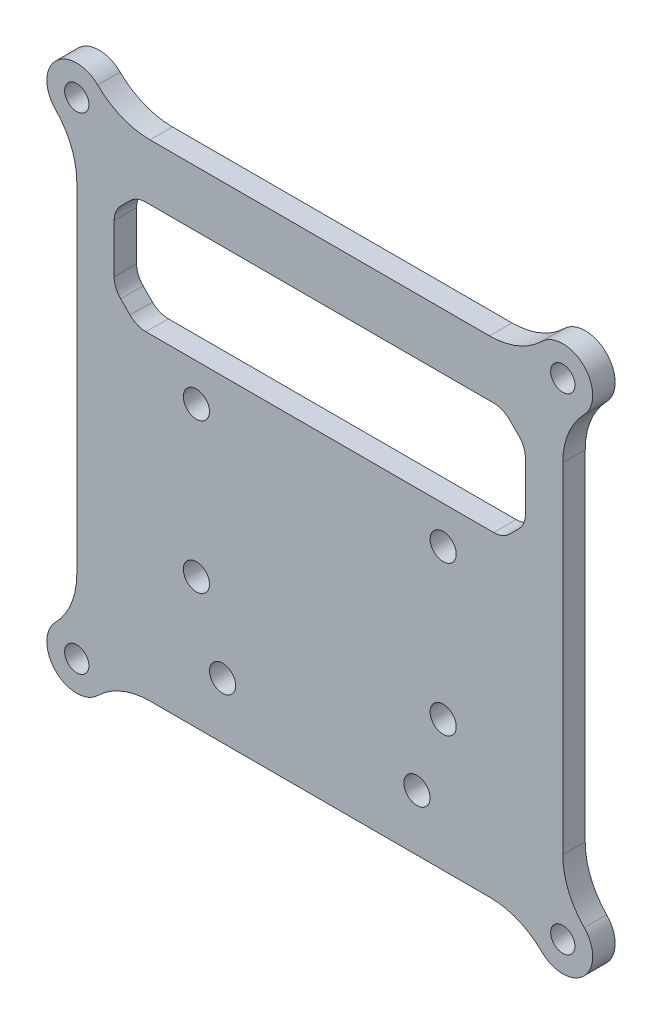
SolidWorks part; units mm, degrees
material "ABS"
ref_plane "Спереди" through (0, 0, 0) normal (0, 0, 1) x (1, 0, 0)
ref_plane "Сверху" through (0, 0, 0) normal (0, 1, 0) x (1, 0, 0)
ref_plane "Справа" through (0, 0, 0) normal (1, 0, 0) x (0, 0, -1)
sketch "Эскиз1" plane through (0, 0, 0) normal (0, 0, 1) x (1, 0, 0)
  line L1 (-32.5, -32.5) -> (32.5, -32.5)
  line L2 (-32.5, -32.5) -> (-32.5, 32.5)
  line L3 (-32.5, 32.5) -> (32.5, 32.5)
  line L4 (32.5, -32.5) -> (32.5, 32.5)
  line L5 (-32.5, -32.5) -> (32.5, 32.5) construction
  line L6 (-32.5, 32.5) -> (32.5, -32.5) construction
  circle A0 centre (-32.5, 32.5) radius 1.625
  arc A1 (-28.5, 32.5) -> (-32.5, 28.5) centre (-32.5, 32.5) ccw
  circle A2 centre (32.5, 32.5) radius 1.625
  arc A3 (32.5, 28.5) -> (28.5, 32.5) centre (32.5, 32.5) ccw
  circle A4 centre (32.5, -32.5) radius 1.625
  arc A5 (28.5, -32.5) -> (32.5, -28.5) centre (32.5, -32.5) ccw
  circle A6 centre (-32.5, -32.5) radius 1.625
  arc A7 (-32.5, -28.5) -> (-28.5, -32.5) centre (-32.5, -32.5) ccw
  point P0 (0, 0)
  point P20 (0, 0)
  dimension "D2" = 3.25
  dimension "D3" = 8
  dimension "D1" = 65
  dimension "D4" = 4
extrude "Бобышка-Вытянуть1" add sketch "Эскиз1" along normal blind 3 contours A6 L1 A4 L4 A2 L3 A0 L2 | L3 A1 L2 A0 | L4 A3 L3 A2 | L1 A5 L4 A4 | L2 A7 L1 A6
fillet "Скругление1" radius 10 8 edges at (-28.5, -32.5, 1.5) (-32.5, -28.5, 1.5) (-28.5, 32.5, 1.5) (-32.5, 28.5, 1.5) (28.5, 32.5, 1.5) (32.5, 28.5, 1.5) (32.5, -28.5, 1.5) (28.5, -32.5, 1.5)
sketch "Эскиз2" plane through (0, 0, 3) normal (0, 0, 1) x (1, 0, 0)
  line L0 (0, 32.5) -> (0, -32.5) construction
  line L1 (-22.702, 32.5) -> (22.702, 32.5) construction
  line L2 (-22.702, -32.5) -> (22.702, -32.5) construction
  line L3 (-15.6432, -25) -> (20.4381, -25) construction
  circle A0 centre (-13, -25) radius 1.75
  circle A1 centre (13, -25) radius 1.75
  dimension "D1" = 3.5
  dimension "D2" = 13
  dimension "D3" = 7.5
sketch "Эскиз3" plane through (0, 0, 3) normal (0, 0, 1) x (1, 0, 0)
  circle A0 centre (0, 0) radius 50
  dimension "D1" = 100
extrude "Вырез-Вытянуть1" cut sketch "Эскиз2" against normal blind 10
sketch "Эскиз4" plane through (0, 0, 3) normal (0, 0, 1) x (1, 0, 0)
  line L0 (0, -32.5) -> (0, 32.5) construction
  line L1 (-22.702, -32.5) -> (22.702, -32.5) construction
  line L2 (-22.702, 32.5) -> (22.702, 32.5) construction
  line L3 (-22.6055, -15) -> (24.9146, -15) construction
  circle A0 centre (-16.5, -15) radius 1.75
  circle A1 centre (16.5, -15) radius 1.75
  dimension "D1" = 3.5
  dimension "D2" = 16.5
  dimension "D3" = 17.5
extrude "Вырез-Вытянуть2" cut sketch "Эскиз4" against normal blind 10
sketch "Эскиз5" plane through (0, 0, 3) normal (0, 0, 1) x (1, 0, 0)
  line L0 (-32.5, 5) -> (32.5, 5) construction
  line L1 (-32.5, -22.702) -> (-32.5, 22.702) construction
  line L2 (32.5, -22.702) -> (32.5, 22.702) construction
  line L3 (0, -32.5) -> (0, 32.5) construction
  line L4 (-22.702, -32.5) -> (22.702, -32.5) construction
  line L5 (-22.702, 32.5) -> (22.702, 32.5) construction
  circle A0 centre (-16.5, 5) radius 1.75
  circle A1 centre (16.5, 5) radius 1.75
  dimension "D1" = 3.5
  dimension "D2" = 16.5
  dimension "D3" = 37.5
extrude "Вырез-Вытянуть3" cut sketch "Эскиз5" against normal blind 10
sketch "Эскиз7" plane through (0, 0, 3) normal (0, 0, 1) x (1, 0, 0)
  line L0 (-32.5, -22.702) -> (-32.5, 22.702) construction
  line L1 (-24.5, 25) -> (24.5, 25)
  line L2 (-27.5, 22) -> (-27.5, 13)
  line L3 (-24.5, 10) -> (24.5, 10)
  line L4 (27.5, 22) -> (27.5, 13)
  line L5 (-27.5, 25) -> (27.5, 10) construction
  line L6 (-27.5, 10) -> (27.5, 25) construction
  line L7 (32.5, -22.702) -> (32.5, 22.702) construction
  line L8 (-27.5, 22) -> (-24.5, 25)
  line L9 (-27.5, 13) -> (-24.5, 10)
  line L10 (24.5, 10) -> (27.5, 13)
  line L11 (24.5, 25) -> (27.5, 22)
  point P0 (0, 17.5)
  dimension "D1" = 5
  dimension "D2" = 5
  dimension "D3" = 5
  dimension "D4" = 15
extrude "Вырез-Вытянуть4" cut sketch "Эскиз7" against normal blind 10
fillet "Скругление2" radius 3 8 edges at (27.5, 22, 1.5) (24.5, 25, 1.5) (27.5, 13, 1.5) (24.5, 10, 1.5) (-24.5, 10, 1.5) (-27.5, 13, 1.5) (-24.5, 25, 1.5) (-27.5, 22, 1.5)
